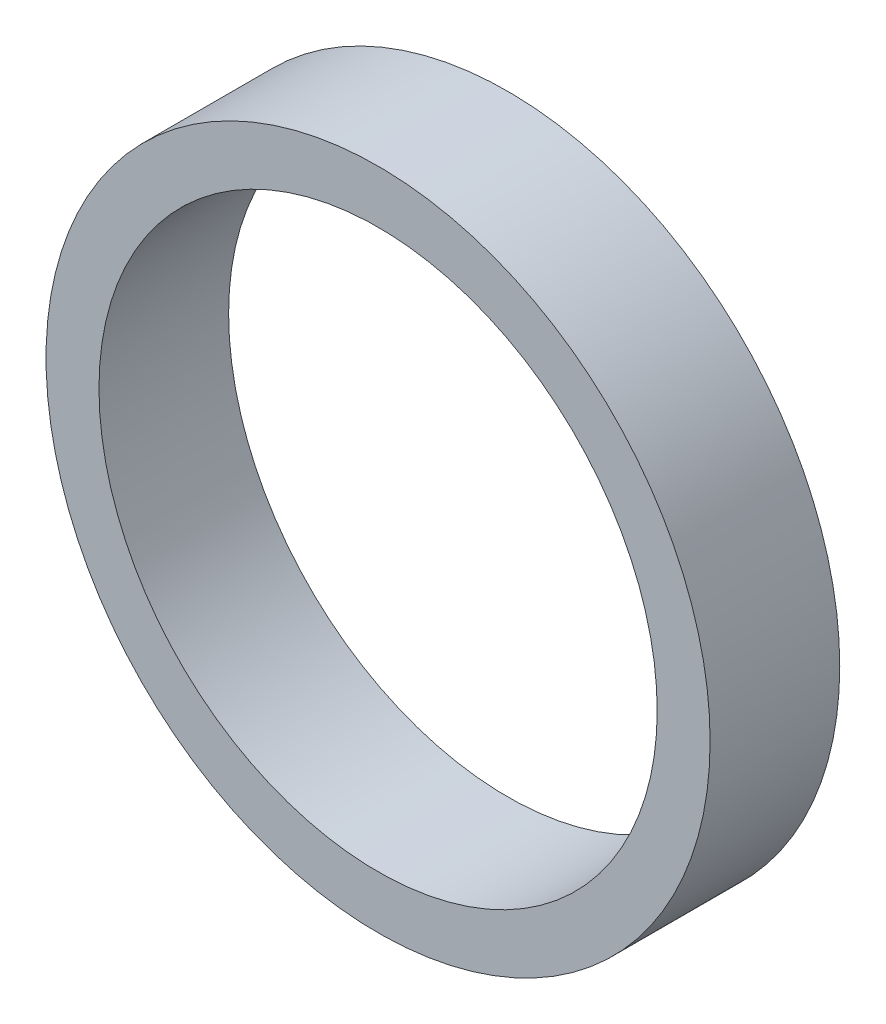
SolidWorks part; units mm, degrees
ref_plane "前视基准面" through (0, 0, 0) normal (0, 0, 1) x (1, 0, 0)
ref_plane "上视基准面" through (0, 0, 0) normal (0, 1, 0) x (1, 0, 0)
ref_plane "右视基准面" through (0, 0, 0) normal (1, 0, 0) x (0, 0, -1)
other "Configuration Table"
sketch "草图1" plane through (0, 0, 0) normal (0, 0, 1) x (1, 0, 0)
  circle A0 centre (0, 0) radius 10.55
  dimension "D1" = 21.1
extrude "拉伸-薄壁1" add sketch "草图1" along normal blind 4.9 thin
